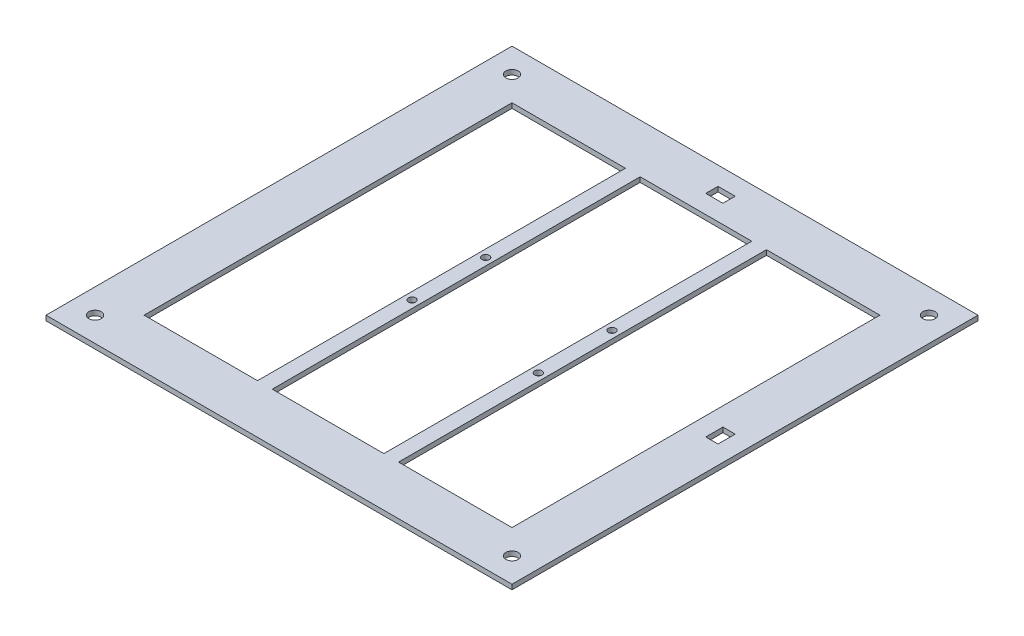
SolidWorks part; units mm, degrees
ref_plane "Alzado" through (0, 0, 0) normal (0, 0, 1) x (1, 0, 0)
ref_plane "Planta" through (0, 0, 0) normal (0, 1, 0) x (1, 0, 0)
ref_plane "Vista lateral" through (0, 0, 0) normal (1, 0, 0) x (0, 0, -1)
sketch "Croquis1" plane through (0, 0, 0) normal (0, 1, 0) x (1, 0, 0)
  line L0 (-10, -10) -> (-10, 180)
  line L1 (0, 0) -> (170, 0) construction
  line L2 (0, 0) -> (0, 170) construction
  line L3 (0, 170) -> (170, 170) construction
  line L4 (170, 0) -> (170, 170) construction
  line L5 (-10, 180) -> (180, 180)
  line L6 (180, -10) -> (180, 180)
  line L7 (-10, -10) -> (180, -10)
  line L8 (10, 10) -> (10, 160)
  line L9 (10, 160) -> (56.25, 160)
  line L10 (160, 10) -> (160, 160)
  line L11 (10, 10) -> (56.25, 10)
  line L12 (10, 85) -> (160, 85) construction
  line L13 (59.25, 85) -> (59.25, 100) construction
  line L14 (59.25, 85) -> (59.25, 70) construction
  line L15 (85, 85) -> (85, 160) construction
  line L16 (56.25, 147.7957) -> (62.25, 147.7957) construction
  line L18 (56.25, 160) -> (56.25, 10)
  line L20 (62.25, 160) -> (62.25, 10)
  line L21 (59.25, 147.7957) -> (59.25, 100) construction
  line L22 (62.25, 160) -> (107.75, 160)
  line L23 (62.25, 10) -> (107.75, 10)
  line L24 (10, 160) -> (160, 160) construction
  line L25 (107.75, 160) -> (107.75, 10)
  line L26 (10, 10) -> (160, 10) construction
  line L27 (113.75, 160) -> (113.75, 10)
  line L28 (113.75, 160) -> (160, 160)
  line L29 (113.75, 10) -> (160, 10)
  line L31 (167.5, 81.5) -> (172.5, 81.5)
  line L32 (167.5, 81.5) -> (167.5, 88.5)
  line L33 (167.5, 88.5) -> (172.5, 88.5)
  line L34 (172.5, 81.5) -> (172.5, 88.5)
  line L35 (167.5, 81.5) -> (172.5, 88.5) construction
  line L36 (167.5, 88.5) -> (172.5, 81.5) construction
  line L37 (81.5, 172.5) -> (88.5, 172.5)
  line L38 (81.5, 172.5) -> (81.5, 167.5)
  line L39 (81.5, 167.5) -> (88.5, 167.5)
  line L40 (88.5, 172.5) -> (88.5, 167.5)
  line L41 (81.5, 172.5) -> (88.5, 167.5) construction
  line L42 (81.5, 167.5) -> (88.5, 172.5) construction
  circle A0 centre (59.25, 100) radius 1.5
  circle A1 centre (59.25, 70) radius 1.5
  circle A2 centre (0, 170) radius 2.5
  circle A3 centre (0, 0) radius 2.5
  circle A4 centre (110.75, 100) radius 1.5
  circle A5 centre (110.75, 70) radius 1.5
  circle A6 centre (170, 0) radius 2.5
  circle A7 centre (170, 170) radius 2.5
  point P41 (170, 85)
  point P46 (85, 170)
  dimension "D4" = 3
  dimension "D8" = 5
  dimension "D1" = 170
  dimension "D2" = 10
  dimension "D5" = 25.75
  dimension "D6" = 15
  dimension "D7" = 6
  dimension "D9" = 5
  dimension "D10" = 7
  dimension "D3" = 10
extrude "Saliente-Extruir1" add sketch "Croquis1" along normal blind 2
